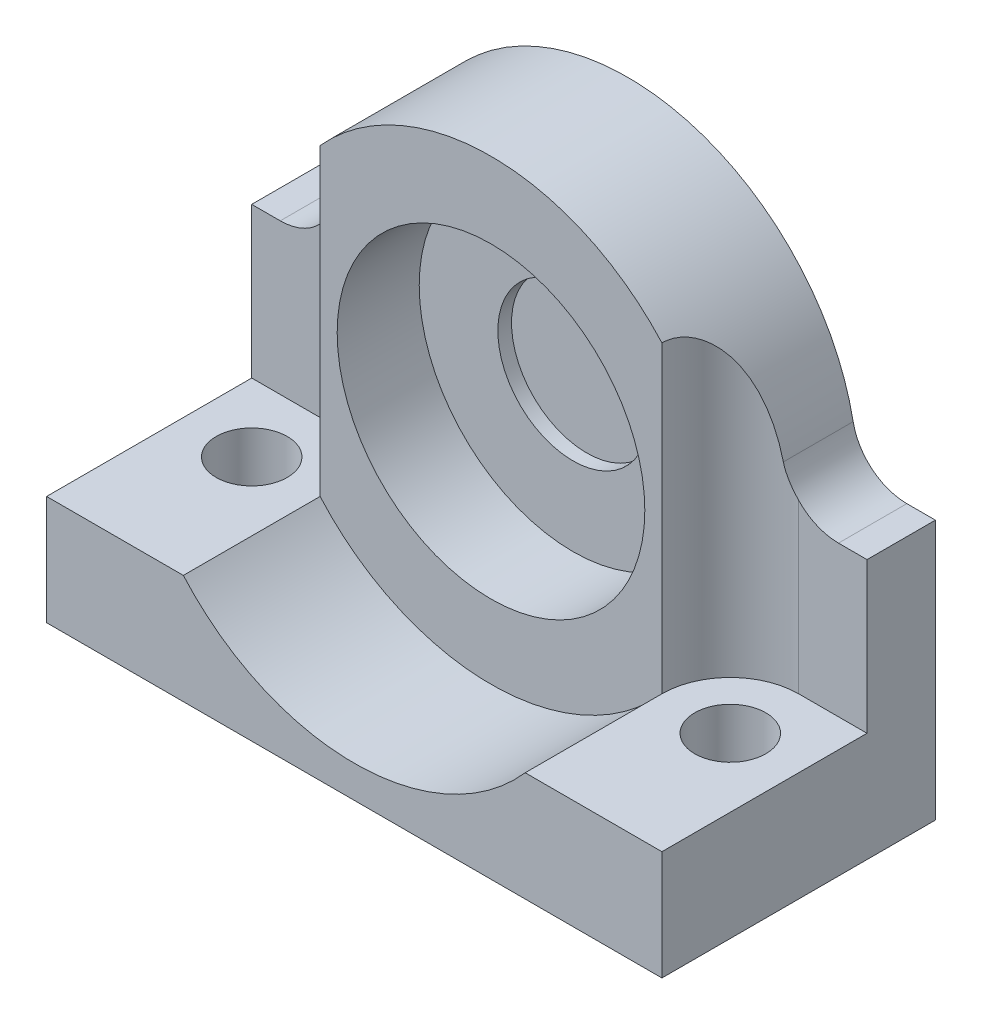
SolidWorks part; units mm, degrees
material "ABS"
ref_plane "Front Plane" through (0, 0, 0) normal (0, 0, 1) x (1, 0, 0)
ref_plane "Top Plane" through (0, 0, 0) normal (0, 1, 0) x (1, 0, 0)
ref_plane "Right Plane" through (0, 0, 0) normal (1, 0, 0) x (0, 0, -1)
sketch "Sketch1" plane through (0, 0, 0) normal (0, 0, 1) x (1, 0, 0)
  line L0 (0, 0) -> (22.5, 0)
  line L1 (22.5, 0) -> (22.5, 19)
  line L2 (22.5, 19) -> (16.8, 19)
  line L3 (-16.8, 19) -> (-22.5, 19)
  line L4 (-22.5, 19) -> (-22.5, 0)
  line L5 (-22.5, 0) -> (0, 0)
  line L6 (0, 19) -> (0, 0) construction
  line L7 (0, 19) -> (16.8, 19) construction
  line L8 (-16.8, 19) -> (0, 19) construction
  arc A0 (16.8, 19) -> (-16.8, 19) centre (0, 19) ccw
  dimension "D2" = 16.8
  dimension "D1" = 45
  dimension "D3" = 19
extrude "Boss-Extrude1" add sketch "Sketch1" along normal blind 20
sketch "Sketch2" plane through (22.5, 0, 0) normal (1, 0, 0) x (0, 0, -1)
  line L0 (-10, 35.8) -> (-10, 8)
  line L1 (0, 35.8) -> (-20, 35.8) construction
  line L2 (-10, 8) -> (-20, 8)
  line L3 (-20, 0) -> (-20, 19) construction
  line L4 (-20, 8) -> (-20, 35.8)
  line L5 (-20, 35.8) -> (-20, 19) construction
  line L6 (-20, 35.8) -> (-10, 35.8)
  line L7 (-20, 0) -> (0, 0) construction
  dimension "D1" = 8
extrude "Cut-Extrude1" cut sketch "Sketch2" against normal through all
sketch "Sketch4" plane through (0, 0, 10) normal (0, 0, 1) x (1, 0, 0)
  circle A0 centre (0, 19) radius 11.25
  dimension "D1" = 22.5
extrude "Cut-Extrude3" cut sketch "Sketch4" against normal blind 6
sketch "Sketch5" plane through (0, 0, 4) normal (0, 0, 1) x (1, 0, 0)
  circle A0 centre (0, 19) radius 5.5
  dimension "D1" = 11
extrude "Cut-Extrude4" cut sketch "Sketch5" against normal blind 1
sketch "Sketch6" plane through (0, 8, 0) normal (0, 1, 0) x (1, 0, 0)
  line L0 (-22.5, -10) -> (-2.3585, -10) construction
  line L1 (2.3585, -10) -> (22.5, -10) construction
  line L2 (-17.5, -5) -> (-22.5, -5)
  line L3 (-22.5, -10) -> (-22.5, 0) construction
  line L4 (-22.5, -5) -> (-22.5, -10)
  line L5 (-22.5, -10) -> (-12.5, -10)
  line L6 (17.5, -5) -> (22.5, -5)
  line L7 (22.5, -10) -> (22.5, 0) construction
  line L8 (22.5, -5) -> (22.5, -10)
  line L9 (22.5, -10) -> (12.5, -10)
  line L10 (-16.8, 0) -> (-22.5, 0) construction
  arc A0 (-12.5, -10) -> (-17.5, -5) centre (-17.5, -10) ccw
  arc A1 (17.5, -5) -> (12.5, -10) centre (17.5, -10) ccw
  dimension "D1" = 5
  dimension "D2" = 5
extrude "Cut-Extrude5" cut sketch "Sketch6" along normal through all
sketch "Sketch7" plane through (0, 8, 0) normal (0, 1, 0) x (1, 0, 0)
  circle A0 centre (-17.5, -10) radius 2.6
  circle A1 centre (17.5, -10) radius 2.6
  dimension "D1" = 5.2
extrude "Cut-Extrude6" cut sketch "Sketch7" against normal through all
sketch "Sketch8" plane through (0, 0, 10) normal (0, 0, 1) x (1, 0, 0)
  line L0 (-12.5, 8) -> (12.5, 8)
  arc A0 (-12.5, 8) -> (12.5, 8) centre (0, 19) ccw
extrude "Cut-Extrude7" cut sketch "Sketch8" along normal through all
fillet "Fillet1" radius 4 2 edges at (16.8, 19, 2.5246) (-16.8, 19, 2.5246)
